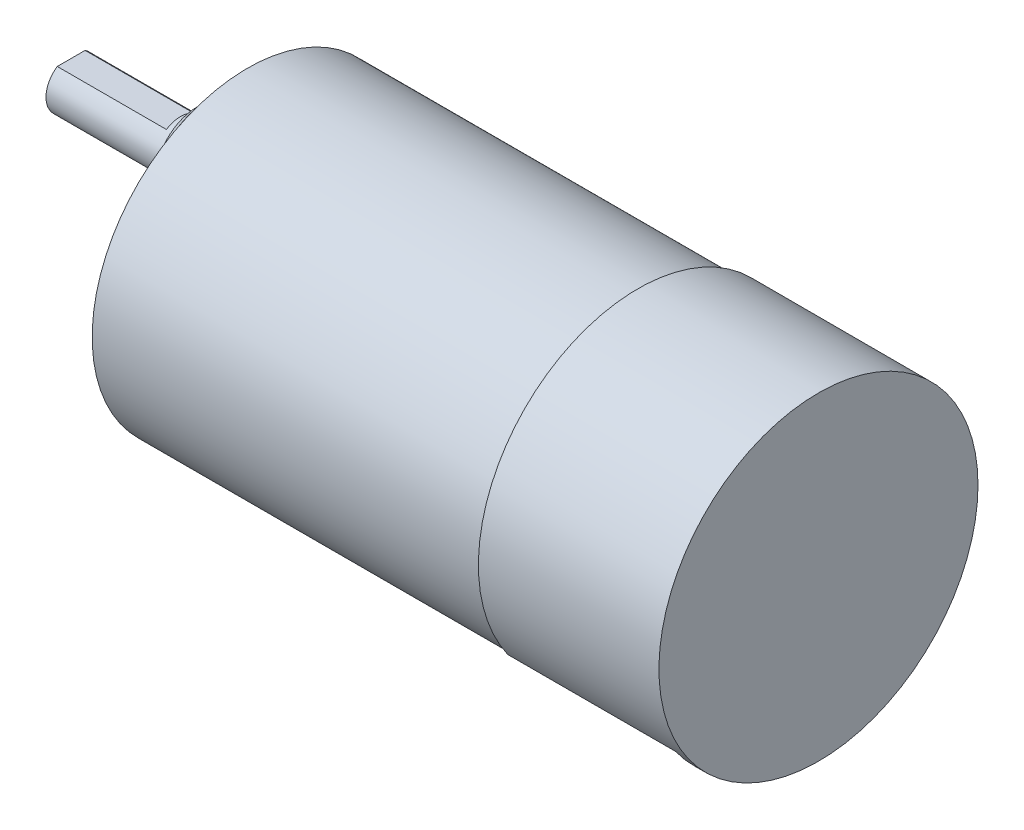
SolidWorks part; units mm, degrees
ref_plane "Front Plane" through (0, 0, 0) normal (0, 0, 1) x (1, 0, 0)
ref_plane "Top Plane" through (0, 0, 0) normal (0, 1, 0) x (1, 0, 0)
ref_plane "Right Plane" through (0, 0, 0) normal (1, 0, 0) x (0, 0, -1)
sketch "Sketch2" plane through (0, 0, 0) normal (1, 0, 0) x (0, 0, -1)
  circle A0 centre (0, 0) radius 18.5
  dimension "D1" = 37
extrude "Boss-Extrude1" add sketch "Sketch2" along normal blind 50
sketch "Sketch3" plane through (0, 0, 0) normal (-1, 0, 0) x (0, 0, 1)
  circle A1 centre (0, 6.5) radius 6
extrude "Boss-Extrude2" add sketch "Sketch3" along normal blind 6 separate body
sketch "Sketch4" plane through (-6, 0, 0) normal (-1, 0, 0) x (0, 0, 1)
  circle A0 centre (0, 6.5) radius 3
  dimension "D1" = 6
extrude "Boss-Extrude3" add sketch "Sketch4" along normal blind 15 separate body
chamfer "Chamfer1" distance 1 angle 45 1 edges at (-6, 6.5, 6)
sketch "Sketch5" plane through (-21, 0, 0) normal (-1, 0, 0) x (0, 0, 1)
  line L1 (1.6583, 9) -> (-1.6583, 9)
  circle A0 centre (0, 6.5) radius 3 construction
  arc A1 (1.6583, 9) -> (-1.6583, 9) centre (0, 6.5) ccw
extrude "Cut-Extrude1" cut sketch "Sketch5" against normal blind 13
sketch "Sketch6" plane through (0, 0, 0) normal (-1, 0, 0) x (0, 0, 1)
  arc A2 (-8.6346, 9.0385) -> (8.6346, 9.0385) centre (0, 0) ccw
  circle A3 centre (0, 6.5) radius 6 construction
  circle A4 centre (0, 6.5) radius 6
  arc A5 (-8.6346, 9.0385) -> (8.6346, 9.0385) centre (0, 6.5) ccw
  circle A6 centre (0, 6.5) radius 9 construction
  dimension "D1" = 3
extrude "Cut-Extrude2" cut sketch "Sketch6" against normal blind 0.5
sketch "Sketch7" plane through (50, 0, 0) normal (1, 0, 0) x (0, 0, -1)
  circle A0 centre (0, 0) radius 18.5 construction
  circle A1 centre (0, 0) radius 18.5
extrude "Cut-Extrude3" cut sketch "Sketch7" against normal blind 3.5
sketch "Sketch8" plane through (46.5, 0, 0) normal (1, 0, 0) x (0, 0, -1)
  circle A0 centre (0, 0) radius 19
  dimension "D1" = 38
extrude "Boss-Extrude4" add sketch "Sketch8" along normal blind 21.5 separate body
sketch "Sketch9" plane through (0, 0, 0) normal (0, 1, 0) x (1, 0, 0)
  line L0 (66.5, 0) -> (68, 0)
  line L1 (46.5, -15.5) -> (66.5, -15.5)
  line L2 (46.5, -15.5) -> (46.5, 15.5)
  line L3 (46.5, 15.5) -> (66.5, 15.5)
  line L4 (66.5, -15.5) -> (66.5, 15.5)
  line L8 (68, -19) -> (68, 19) construction
  point P0 (45.2198, 6.3027)
  dimension "D1" = 31
  dimension "D2" = 20
extrude "Cut-Extrude4" cut sketch "Sketch9" against normal blind 21.5 contours L3 L4 L1 L2
